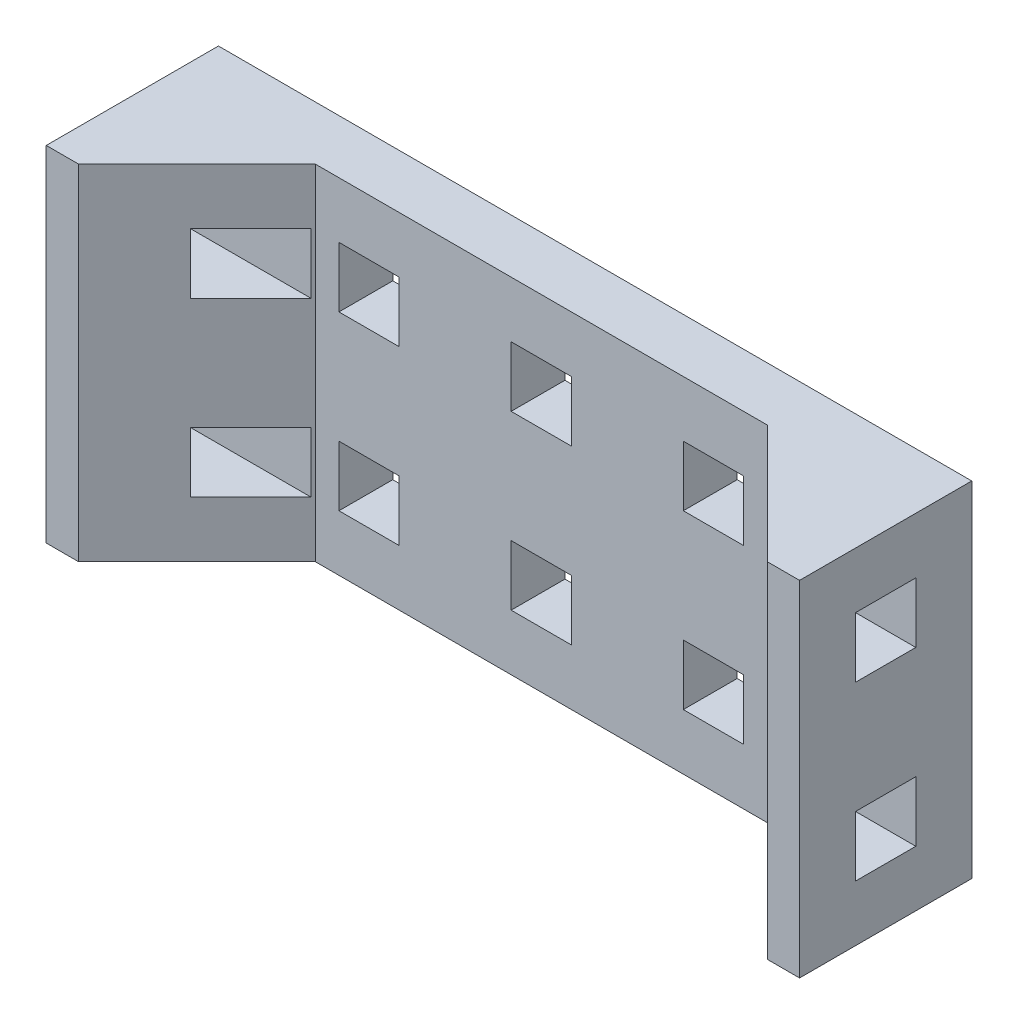
SolidWorks part; units mm, degrees
ref_plane "Plano frontal" through (0, 0, 0) normal (0, 0, 1) x (1, 0, 0)
ref_plane "Plano superior" through (0, 0, 0) normal (0, 1, 0) x (1, 0, 0)
ref_plane "Plano direito" through (0, 0, 0) normal (1, 0, 0) x (0, 0, -1)
sketch "Esboço1" plane through (0, 0, 0) normal (0, 0, 1) x (1, 0, 0)
  line L0 (-25, 0) -> (25, 0)
  line L1 (25, 0) -> (25, 8)
  line L2 (25, 8) -> (23.5, 8)
  line L3 (23.5, 8) -> (18, 2.5)
  line L4 (18, 2.5) -> (-18, 2.5)
  line L5 (0, 0) -> (0, 2.5) construction
  line L6 (-23.5, 8) -> (-18, 2.5)
  line L7 (-25, 8) -> (-23.5, 8)
  line L8 (-25, 0) -> (-25, 8)
  dimension "D1" = 45
  dimension "D2" = 2.5
  dimension "D3" = 1.5
  dimension "D4" = 8
extrude "Ressalto-extrusão1" add sketch "Esboço1" along normal blind 16
sketch "Esboço2" plane through (25, 0, 0) normal (1, 0, 0) x (0, 0, -1)
  line L0 (-8, 0) -> (-8, 4) construction
  line L1 (-16, 0) -> (0, 0) construction
  line L2 (-8, 4) -> (-4, 4) construction
  line L3 (-8, 4) -> (-12, 4) construction
  line L4 (-5.4, 5.4) -> (-5.4, 2.6)
  line L5 (-13.4, 5.4) -> (-10.6, 5.4)
  line L6 (-13.4, 5.4) -> (-13.4, 2.6)
  line L7 (-13.4, 2.6) -> (-10.6, 2.6)
  line L8 (-10.6, 5.4) -> (-10.6, 2.6)
  line L9 (-13.4, 5.4) -> (-10.6, 2.6) construction
  line L10 (-13.4, 2.6) -> (-10.6, 5.4) construction
  line L11 (-5.4, 5.4) -> (-2.6, 5.4)
  line L12 (-5.4, 5.4) -> (-2.6, 2.6) construction
  line L13 (-5.4, 2.6) -> (-2.6, 2.6)
  line L14 (-2.6, 5.4) -> (-2.6, 2.6)
  line L15 (-5.4, 2.6) -> (-2.6, 5.4) construction
extrude "Corte-extrusão1" cut sketch "Esboço2" against normal through all
sketch "Esboço3" plane through (0, 2.5, 0) normal (0, 1, 0) x (1, 0, 0)
  line L0 (0, 0) -> (0, -16) construction
  line L1 (18, -16) -> (-18, -16) construction
  line L3 (-14, -3) -> (14, -3)
  line L4 (-14, -3) -> (-14, -13)
  line L5 (-14, -13) -> (14, -13)
  line L6 (14, -3) -> (14, -13)
  line L7 (-14, -3) -> (14, -13) construction
  line L8 (-14, -13) -> (14, -3) construction
  point P5 (0, -8)
sketch "Esboço4" plane through (0, 2.5, 0) normal (0, 1, 0) x (1, 0, 0)
  line L0 (0, -8) -> (-16, -8) construction
  line L1 (-16, -8) -> (-16, -4) construction
  line L2 (-9.4, -2.6) -> (-6.6, -5.4) construction
  line L3 (-17.4, -2.6) -> (-14.6, -2.6)
  line L4 (-17.4, -2.6) -> (-17.4, -5.4)
  line L5 (-17.4, -5.4) -> (-14.6, -5.4)
  line L6 (-14.6, -2.6) -> (-14.6, -5.4)
  line L7 (-17.4, -2.6) -> (-14.6, -5.4) construction
  line L8 (-17.4, -5.4) -> (-14.6, -2.6) construction
  line L9 (-9.4, -5.4) -> (-6.6, -2.6) construction
  line L10 (-9.4, -2.6) -> (-9.4, -5.4)
  line L11 (-9.4, -2.6) -> (-6.6, -2.6)
  line L12 (-6.6, -2.6) -> (-6.6, -5.4)
  line L13 (-9.4, -5.4) -> (-6.6, -5.4)
  line L14 (-1.4, -2.6) -> (1.4, -5.4) construction
  line L15 (-1.4, -5.4) -> (1.4, -2.6) construction
  line L16 (-1.4, -2.6) -> (-1.4, -5.4)
  line L17 (-1.4, -2.6) -> (1.4, -2.6)
  line L18 (1.4, -2.6) -> (1.4, -5.4)
  line L19 (-1.4, -5.4) -> (1.4, -5.4)
  line L20 (6.6, -2.6) -> (9.4, -5.4) construction
  line L21 (6.6, -5.4) -> (9.4, -2.6) construction
  line L22 (6.6, -2.6) -> (6.6, -5.4)
  line L23 (6.6, -2.6) -> (9.4, -2.6)
  line L24 (9.4, -2.6) -> (9.4, -5.4)
  line L25 (6.6, -5.4) -> (9.4, -5.4)
  line L26 (14.6, -2.6) -> (17.4, -5.4) construction
  line L27 (14.6, -5.4) -> (17.4, -2.6) construction
  line L28 (14.6, -2.6) -> (14.6, -5.4)
  line L29 (14.6, -2.6) -> (17.4, -2.6)
  line L30 (17.4, -2.6) -> (17.4, -5.4)
  line L31 (14.6, -5.4) -> (17.4, -5.4)
  line L32 (-9.4, -10.6) -> (-6.6, -13.4) construction
  line L33 (-9.4, -13.4) -> (-6.6, -10.6) construction
  line L34 (-9.4, -10.6) -> (-9.4, -13.4)
  line L35 (-9.4, -10.6) -> (-6.6, -10.6)
  line L36 (-6.6, -10.6) -> (-6.6, -13.4)
  line L37 (-9.4, -13.4) -> (-6.6, -13.4)
  line L38 (-1.4, -10.6) -> (1.4, -13.4) construction
  line L39 (-1.4, -13.4) -> (1.4, -10.6) construction
  line L40 (-1.4, -10.6) -> (-1.4, -13.4)
  line L41 (-1.4, -10.6) -> (1.4, -10.6)
  line L42 (1.4, -10.6) -> (1.4, -13.4)
  line L43 (-1.4, -13.4) -> (1.4, -13.4)
  line L44 (6.6, -10.6) -> (9.4, -13.4) construction
  line L45 (6.6, -13.4) -> (9.4, -10.6) construction
  line L46 (6.6, -10.6) -> (6.6, -13.4)
  line L47 (6.6, -10.6) -> (9.4, -10.6)
  line L48 (9.4, -10.6) -> (9.4, -13.4)
  line L49 (6.6, -13.4) -> (9.4, -13.4)
  line L50 (14.6, -10.6) -> (17.4, -13.4) construction
  line L51 (14.6, -13.4) -> (17.4, -10.6) construction
  line L52 (14.6, -10.6) -> (14.6, -13.4)
  line L53 (14.6, -10.6) -> (17.4, -10.6)
  line L54 (17.4, -10.6) -> (17.4, -13.4)
  line L55 (14.6, -13.4) -> (17.4, -13.4)
  line L56 (-17.4, -10.6) -> (-14.6, -13.4) construction
  line L57 (-17.4, -13.4) -> (-14.6, -10.6) construction
  line L58 (-17.4, -10.6) -> (-17.4, -13.4)
  line L59 (-17.4, -10.6) -> (-14.6, -10.6)
  line L60 (-14.6, -10.6) -> (-14.6, -13.4)
  line L61 (-17.4, -13.4) -> (-14.6, -13.4)
  dimension "D1" = 5
  dimension "D2" = 2
extrude "Corte-extrusão2" cut sketch "Esboço4" against normal through all
move or copy body "Corpo-Mover/Copiar1" bodies to move or copy 104 copy no rotation origin (0, 4, 8) rotation axis (1, 0, 0) rotation angle 90
sketch "Esboço6" plane through (0, 0, 4) normal (0, 0, -1) x (-1, 0, 0)
  line L1 (25, -4) -> (-25, -4) construction
  line L2 (7.5, -4) -> (7.5, 12)
  line L3 (25, 12) -> (-25, 12) construction
  line L4 (7.5, 12) -> (-25, 12)
  line L5 (-25, 12) -> (-25, -4)
  line L6 (7.5, -4) -> (-25, -4)
extrude "Corte-extrusão3" cut sketch "Esboço6" against normal through all
mirror "Espelhar3" about plane through (-7.5, -4, 12) normal (-1, 0, 0) of bodies 106
sketch "Esboço7" plane through (0, 0, 6.5) normal (0, 0, 1) x (1, 0, 0)
  line L1 (-17.582, 9.9145) -> (7.6394, 9.9145)
  line L2 (-17.582, 9.9145) -> (-17.582, -2.6616)
  line L3 (-17.582, -2.6616) -> (7.6394, -2.6616)
  line L4 (7.6394, 9.9145) -> (7.6394, -2.6616)
extrude "Ressalto-extrusão2" add sketch "Esboço7" against normal through all
sketch "Esboço8" plane through (0, 0, 6.5) normal (0, 0, 1) x (1, 0, 0)
  line L0 (-7.5, -4) -> (-7.5, 12) construction
  line L1 (3, -4) -> (-18, -4) construction
  line L2 (3, 12) -> (-18, 12) construction
  line L3 (-7.5, 4) -> (-7.5, 8) construction
  line L4 (-7.5, 8) -> (-15.5, 8) construction
  line L5 (-8.9, 9.4) -> (-6.1, 9.4)
  line L6 (-16.9, 9.4) -> (-14.1, 9.4)
  line L7 (-16.9, 9.4) -> (-16.9, 6.6)
  line L8 (-16.9, 6.6) -> (-14.1, 6.6)
  line L9 (-14.1, 9.4) -> (-14.1, 6.6)
  line L10 (-16.9, 9.4) -> (-14.1, 6.6) construction
  line L11 (-16.9, 6.6) -> (-14.1, 9.4) construction
  line L12 (-8.9, 9.4) -> (-8.9, 6.6)
  line L13 (-8.9, 6.6) -> (-6.1, 6.6)
  line L14 (-6.1, 9.4) -> (-6.1, 6.6)
  line L15 (-8.9, 9.4) -> (-6.1, 6.6) construction
  line L16 (-8.9, 6.6) -> (-6.1, 9.4) construction
  line L17 (-0.9, 9.4) -> (1.9, 9.4)
  line L18 (-0.9, 9.4) -> (-0.9, 6.6)
  line L19 (-0.9, 6.6) -> (1.9, 6.6)
  line L20 (1.9, 9.4) -> (1.9, 6.6)
  line L21 (-0.9, 9.4) -> (1.9, 6.6) construction
  line L22 (-0.9, 6.6) -> (1.9, 9.4) construction
  line L23 (-8.9, 1.4) -> (-6.1, 1.4)
  line L24 (-8.9, 1.4) -> (-8.9, -1.4)
  line L25 (-8.9, -1.4) -> (-6.1, -1.4)
  line L26 (-6.1, 1.4) -> (-6.1, -1.4)
  line L27 (-8.9, 1.4) -> (-6.1, -1.4) construction
  line L28 (-8.9, -1.4) -> (-6.1, 1.4) construction
  line L29 (-0.9, 1.4) -> (1.9, 1.4)
  line L30 (-0.9, 1.4) -> (-0.9, -1.4)
  line L31 (-0.9, -1.4) -> (1.9, -1.4)
  line L32 (1.9, 1.4) -> (1.9, -1.4)
  line L33 (-0.9, 1.4) -> (1.9, -1.4) construction
  line L34 (-0.9, -1.4) -> (1.9, 1.4) construction
  line L35 (-16.9, 1.4) -> (-14.1, 1.4)
  line L36 (-16.9, 1.4) -> (-16.9, -1.4)
  line L37 (-16.9, -1.4) -> (-14.1, -1.4)
  line L38 (-14.1, 1.4) -> (-14.1, -1.4)
  line L39 (-16.9, 1.4) -> (-14.1, -1.4) construction
  line L40 (-16.9, -1.4) -> (-14.1, 1.4) construction
  dimension "D1" = 4
  dimension "D2" = 8
  dimension "D3" = 2.8
  dimension "D4" = 3
  dimension "D5" = 2
extrude "Corte-extrusão4" cut sketch "Esboço8" against normal through all
